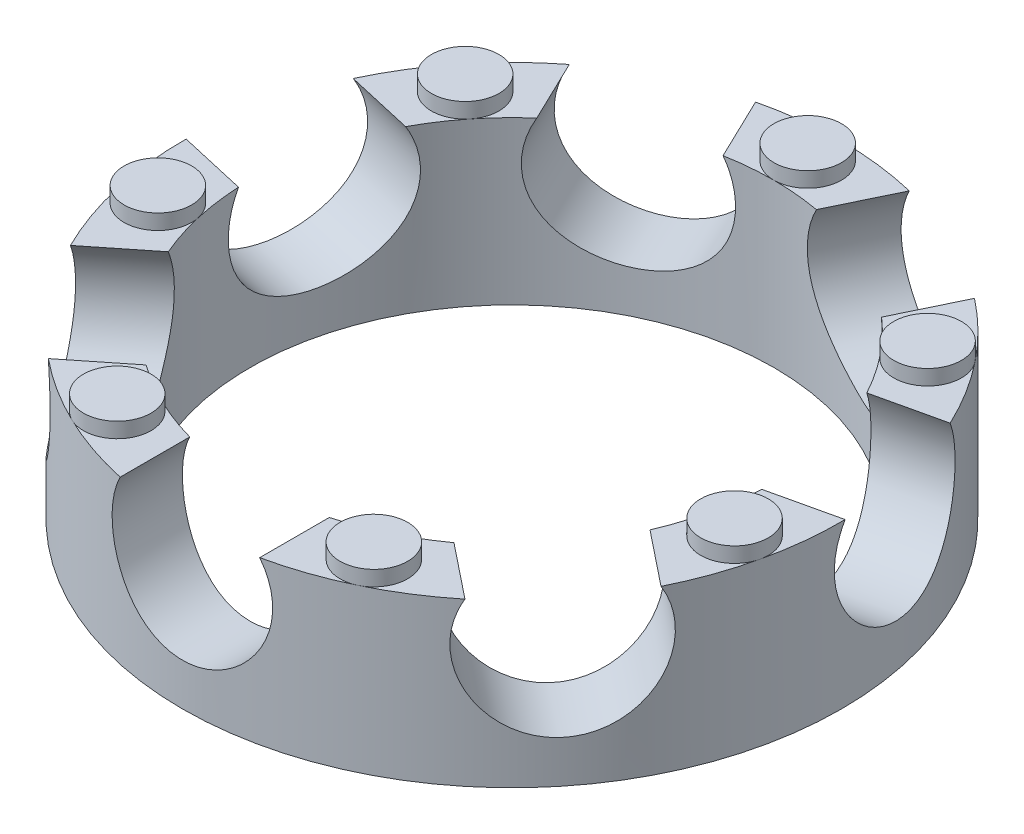
SolidWorks part; units mm, degrees
material "ABS"
ref_plane "Front Plane" through (0, 0, 0) normal (0, 0, 1) x (1, 0, 0)
ref_plane "Top Plane" through (0, 0, 0) normal (0, 1, 0) x (1, 0, 0)
ref_plane "Right Plane" through (0, 0, 0) normal (1, 0, 0) x (0, 0, -1)
sketch "Sketch1" plane through (0, 0, 0) normal (0, 1, 0) x (1, 0, 0)
  circle A0 centre (0, 0) radius 4.953
  dimension "D1" = 9.906
extrude "Boss-Extrude1" add sketch "Sketch1" along normal blind 2.4384
sketch "Sketch2" plane through (0, 2.4384, 0) normal (0, 1, 0) x (1, 0, 0)
  circle A0 centre (0, 0) radius 3.937
  dimension "D1" = 7.874
extrude "Cut-Extrude1" cut sketch "Sketch2" against normal blind 2.4384
sketch "Sketch3" plane through (0, 0, 0) normal (0, 1, 0) x (1, 0, 0)
  line L0 (0, 4.445) -> (0, 0) construction
  line L1 (0, 0) -> (3.4752, 2.7714) construction
  circle A0 centre (0, 4.445) radius 0.508
  circle A1 centre (0, 0) radius 4.953 construction
  circle A2 centre (0, 0) radius 3.937 construction
  circle A3 centre (3.4752, 2.7714) radius 0.508
  circle A4 centre (4.3336, -0.9891) radius 0.508
  circle A5 centre (1.9286, -4.0048) radius 0.508
  circle A6 centre (-1.9286, -4.0048) radius 0.508
  circle A7 centre (-4.3336, -0.9891) radius 0.508
  circle A8 centre (-3.4752, 2.7714) radius 0.508
  point P21 (0, 0)
  dimension "D1" = 51.429
  dimension "D2" = 7
extrude "Boss-Extrude2" add sketch "Sketch3" along normal blind 2.667
sketch "Sketch4" plane through (0, 0, 0) normal (0, 0, 1) x (1, 0, 0)
  line L0 (-4.953, 0) -> (4.953, 0) construction
  circle A0 centre (0, 1.8415) radius 1.2065
  dimension "D1" = 0.635
  dimension "D2" = 2.413
extrude "Cut-Extrude2" cut sketch "Sketch4" along normal up to surface (4.8038 mm away)
sketch "Sketch5" plane through (0, 0, 0) normal (0, 0, 1) x (1, 0, 0)
  line L0 (0, 0) -> (0, 2.667) construction
  line L1 (0.508, 2.667) -> (-0.508, 2.667) construction
pattern_circular "CirPattern1" count 7 over 360 of "Cut-Extrude2"
